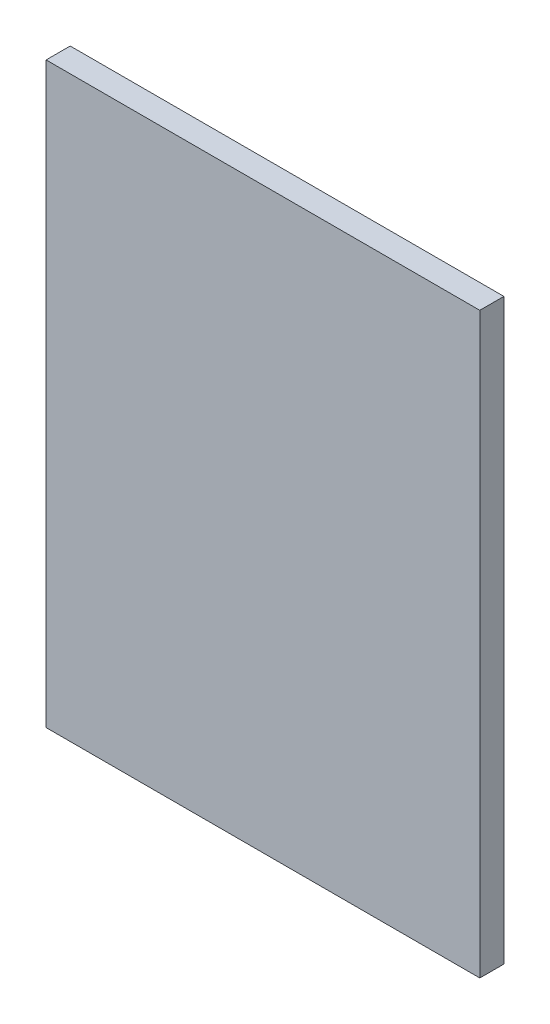
SolidWorks part; units mm, degrees
ref_plane "Front Plane" through (0, 0, 0) normal (0, 0, 1) x (1, 0, 0)
ref_plane "Top Plane" through (0, 0, 0) normal (0, 1, 0) x (1, 0, 0)
ref_plane "Right Plane" through (0, 0, 0) normal (1, 0, 0) x (0, 0, -1)
sketch "Sketch1" plane through (0, 0, 0) normal (0, 0, 1) x (1, 0, 0)
  line L1 (0, 0) -> (228.6, 0)
  line L2 (0, 0) -> (0, 304.8)
  line L3 (0, 304.8) -> (228.6, 304.8)
  line L4 (228.6, 0) -> (228.6, 304.8)
  dimension "D1" = 304.8
  dimension "D2" = 228.6
extrude "Boss-Extrude1" add sketch "Sketch1" along normal blind 12.7
